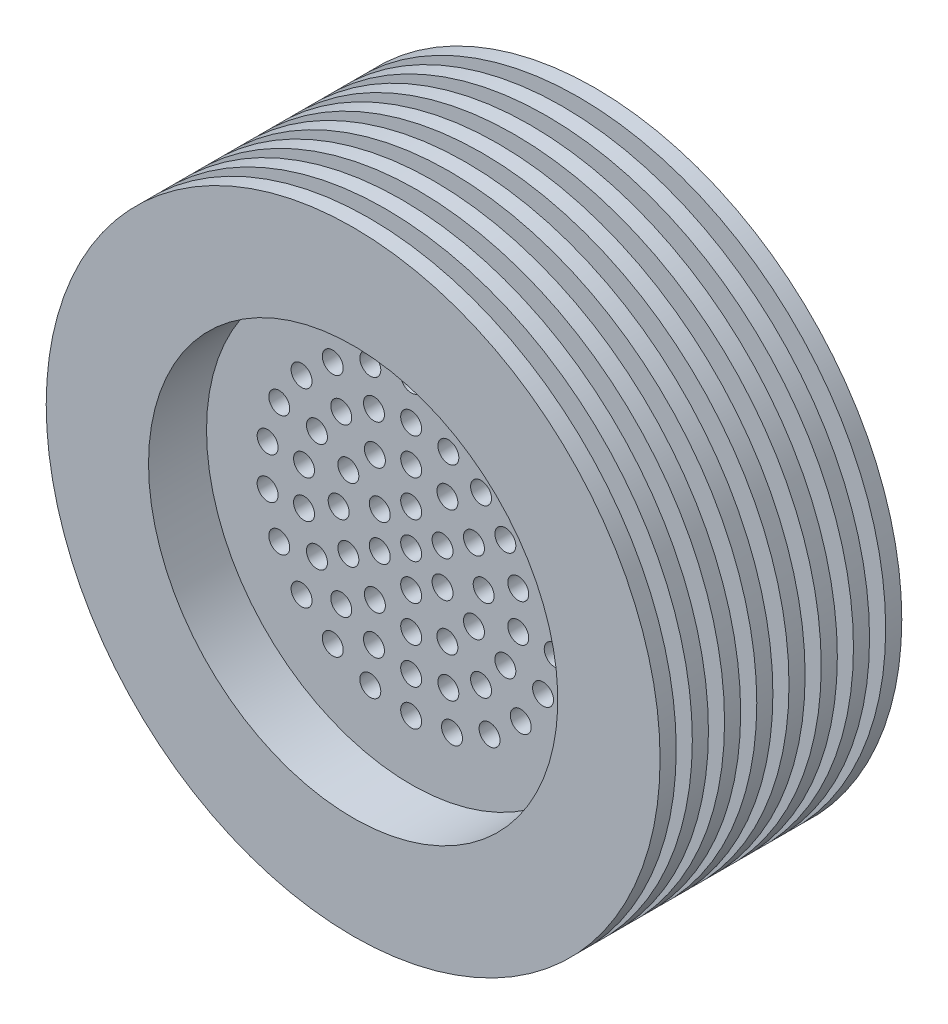
SolidWorks part; units mm, degrees
ref_plane "Plan de face" through (0, 0, 0) normal (0, 0, 1) x (1, 0, 0)
ref_plane "Plan de dessus" through (0, 0, 0) normal (0, 1, 0) x (1, 0, 0)
ref_plane "Plan de droite" through (0, 0, 0) normal (1, 0, 0) x (0, 0, -1)
sketch "Esquisse1" plane through (0, 0, 0) normal (0, 0, 1) x (1, 0, 0)
  circle A0 centre (0, 0) radius 38.1
extrude "Boss.-Extru.1" add sketch "Esquisse1" along normal blind 32
sketch "Esquisse2" plane through (0, 0, 0) normal (0, 0, -1) x (-1, 0, 0)
  circle A0 centre (0, 0) radius 25.4
extrude "Enlèv. mat.-Extru.1" cut sketch "Esquisse2" against normal blind 12.1
sketch "Esquisse3" plane through (0, 0, 12.1) normal (0, 0, -1) x (-1, 0, 0)
  circle A0 centre (0, 0) radius 1.3
  circle A1 centre (0, 4.5) radius 1.3
  circle A2 centre (0, 9) radius 1.3
  circle A3 centre (0, 13.5) radius 1.3
  circle A4 centre (0, 18) radius 1.3
  circle A5 centre (3.8971, 2.25) radius 1.3
  circle A6 centre (3.8971, -2.25) radius 1.3
  circle A7 centre (0, -4.5) radius 1.3
  circle A8 centre (-3.8971, -2.25) radius 1.3
  circle A9 centre (-3.8971, 2.25) radius 1.3
  circle A10 centre (4.5, 7.7942) radius 1.3
  circle A11 centre (7.7942, 4.5) radius 1.3
  circle A12 centre (9, 0) radius 1.3
  circle A13 centre (7.7942, -4.5) radius 1.3
  circle A14 centre (4.5, -7.7942) radius 1.3
  circle A15 centre (0, -9) radius 1.3
  circle A16 centre (-4.5, -7.7942) radius 1.3
  circle A17 centre (-7.7942, -4.5) radius 1.3
  circle A18 centre (-9, 0) radius 1.3
  circle A19 centre (-7.7942, 4.5) radius 1.3
  circle A20 centre (-4.5, 7.7942) radius 1.3
  circle A21 centre (4.6173, 12.6859) radius 1.3
  circle A22 centre (8.6776, 10.3416) radius 1.3
  circle A23 centre (11.6913, 6.75) radius 1.3
  circle A24 centre (13.2949, 2.3443) radius 1.3
  circle A25 centre (13.2949, -2.3443) radius 1.3
  circle A26 centre (11.6913, -6.75) radius 1.3
  circle A27 centre (8.6776, -10.3416) radius 1.3
  circle A28 centre (4.6173, -12.6859) radius 1.3
  circle A29 centre (0, -13.5) radius 1.3
  circle A30 centre (-4.6173, -12.6859) radius 1.3
  circle A31 centre (-8.6776, -10.3416) radius 1.3
  circle A32 centre (-11.6913, -6.75) radius 1.3
  circle A33 centre (-13.2949, -2.3443) radius 1.3
  circle A34 centre (-13.2949, 2.3443) radius 1.3
  circle A35 centre (-11.6913, 6.75) radius 1.3
  circle A36 centre (-8.6776, 10.3416) radius 1.3
  circle A37 centre (-4.6173, 12.6859) radius 1.3
  circle A38 centre (5.0712, 17.2709) radius 1.3
  circle A39 centre (9.7315, 15.1426) radius 1.3
  circle A40 centre (13.6035, 11.7875) radius 1.3
  circle A41 centre (16.3734, 7.4775) radius 1.3
  circle A42 centre (17.8168, 2.5617) radius 1.3
  circle A43 centre (17.8168, -2.5617) radius 1.3
  circle A44 centre (16.3734, -7.4775) radius 1.3
  circle A45 centre (13.6035, -11.7875) radius 1.3
  circle A46 centre (9.7315, -15.1426) radius 1.3
  circle A47 centre (5.0712, -17.2709) radius 1.3
  circle A48 centre (0, -18) radius 1.3
  circle A49 centre (-5.0712, -17.2709) radius 1.3
  circle A50 centre (-9.7315, -15.1426) radius 1.3
  circle A51 centre (-13.6035, -11.7875) radius 1.3
  circle A52 centre (-16.3734, -7.4775) radius 1.3
  circle A53 centre (-17.8168, -2.5617) radius 1.3
  circle A54 centre (-17.8168, 2.5617) radius 1.3
  circle A55 centre (-16.3734, 7.4775) radius 1.3
  circle A56 centre (-13.6035, 11.7875) radius 1.3
  circle A57 centre (-9.7315, 15.1426) radius 1.3
  circle A58 centre (-5.0712, 17.2709) radius 1.3
  point P23 (0, 0)
  point P46 (0, 0)
  point P81 (0, 0)
  point P124 (0, 0)
  dimension "D1" = 5
  dimension "D2" = 6
  dimension "D3" = 12
  dimension "D4" = 18
  dimension "D5" = 22
extrude "Enlèv. mat.-Extru.2" cut sketch "Esquisse3" against normal blind 12.7
sketch "Esquisse4" plane through (0, 0, 24.8) normal (0, 0, -1) x (-1, 0, 0)
  circle A0 centre (0, 0) radius 25.4
extrude "Enlèv. mat.-Extru.3" cut sketch "Esquisse4" against normal through all
sketch "Esquisse5" plane through (0, 0, 0) normal (0, 0, -1) x (-1, 0, 0)
  circle A0 centre (0, 0) radius 34.925
extrude "Enlèv. mat.-Extru.4" cut sketch "Esquisse5" against normal blind 2 flip side to cut
pattern_linear "Répétition linéaire1" count 8 spacing 4 along (0, 0, 1) of "Enlèv. mat.-Extru.4"
